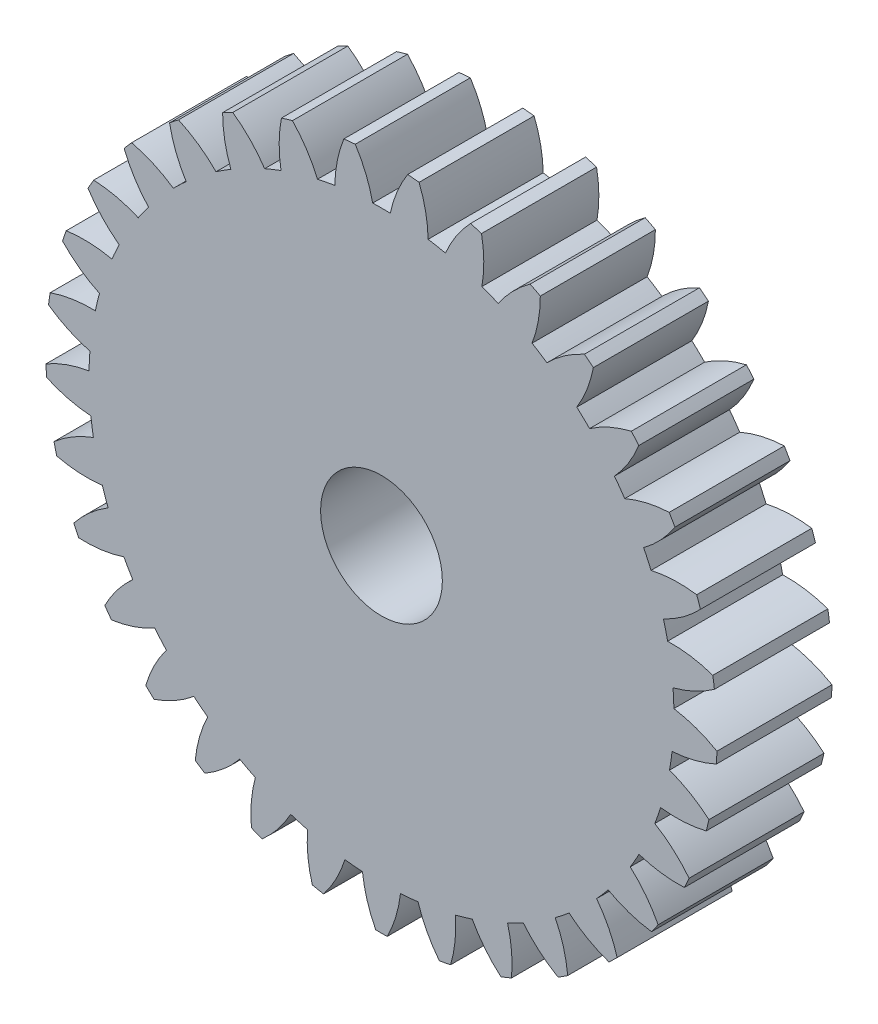
SolidWorks part; units mm, degrees
ref_plane "Alzado" through (0, 0, 0) normal (0, 0, 1) x (1, 0, 0)
ref_plane "Planta" through (0, 0, 0) normal (0, 1, 0) x (1, 0, 0)
ref_plane "Vista lateral" through (0, 0, 0) normal (1, 0, 0) x (0, 0, -1)
sketch "Croquis1" plane through (0, 0, 0) normal (0, 0, 1) x (1, 0, 0)
  line L0 (13.6206, 0) -> (-13.971, 0) construction
  line L1 (-0.46, 15.2421) -> (0, 0) construction
  line L2 (0.46, 15.2421) -> (0, 0) construction
  line L3 (1.3662, 17.4466) -> (0, 0) construction
  line L4 (1.9603, 17.3899) -> (0, 0) construction
  line L5 (0, -3.6901) -> (0, 21.5552) construction
  circle A0 centre (0, 0) radius 3.175
  arc A29 (2.4329, 15.0537) -> (1.9603, 17.3899) centre (-4.1661, 14.9347) ccw
  arc A30 (1.9603, 17.3899) -> (1.3662, 17.4466) centre (0, 0) ccw
  arc A31 (1.3662, 17.4466) -> (0.46, 15.2421) centre (6.9172, 13.8764) ccw
  arc A32 (0.46, 15.2421) -> (-0.46, 15.2421) centre (0, 0) ccw
  circle A133 centre (0, 0) radius 15.249 construction
  circle A134 centre (0, 0) radius 17.5 construction
  arc A135 (3.3363, 14.8796) -> (2.4329, 15.0537) centre (0, 0) ccw
  arc A136 (4.6433, 16.8728) -> (3.3363, 14.8796) centre (9.4183, 12.3166) ccw
  arc A137 (5.2159, 16.7046) -> (4.6433, 16.8728) centre (0, 0) ccw
  arc A138 (5.2378, 14.3212) -> (5.2159, 16.7046) centre (-1.2644, 15.4533) ccw
  arc A139 (6.092, 13.9793) -> (5.2378, 14.3212) centre (0, 0) ccw
  arc A140 (7.7526, 15.6891) -> (6.092, 13.9793) centre (11.5791, 10.3116) ccw
  arc A141 (8.283, 15.4156) -> (7.7526, 15.6891) centre (0, 0) ccw
  arc A142 (7.8535, 13.0712) -> (8.283, 15.4156) centre (1.683, 15.4133) ccw
  arc A143 (8.6275, 12.5737) -> (7.8535, 13.0712) centre (0, 0) ccw
  arc A144 (10.5816, 13.9384) -> (8.6275, 12.5737) centre (13.3213, 7.9339) ccw
  arc A145 (11.0508, 13.5695) -> (10.5816, 13.9384) centre (0, 0) ccw
  arc A146 (10.1853, 11.3487) -> (11.0508, 13.5695) centre (4.5696, 14.8163) ccw
  arc A147 (10.8512, 10.7137) -> (10.1853, 11.3487) centre (0, 0) ccw
  arc A148 (13.0283, 11.6839) -> (10.8512, 10.7137) centre (14.582, 5.2694) ccw
  arc A149 (13.4191, 11.2329) -> (13.0283, 11.6839) centre (0, 0) ccw
  arc A150 (12.149, 9.216) -> (13.4191, 11.2329) centre (7.291, 13.6837) ccw
  arc A151 (12.6827, 8.4665) -> (12.149, 9.216) centre (0, 0) ccw
  arc A152 (15.004, 9.0072) -> (12.6827, 8.4665) centre (15.3158, 2.4145) ccw
  arc A153 (15.3024, 8.4903) -> (15.004, 9.0072) centre (0, 0) ccw
  arc A154 (13.6736, 6.7502) -> (15.3024, 8.4903) centre (9.7489, 12.0566) ccw
  arc A155 (14.0558, 5.9133) -> (13.6736, 6.7502) centre (0, 0) ccw
  arc A156 (16.4375, 6.0049) -> (14.0558, 5.9133) centre (15.4959, -0.5276) ccw
  arc A157 (16.6327, 5.4409) -> (16.4375, 6.0049) centre (0, 0) ccw
  arc A158 (14.704, 4.0405) -> (16.6327, 5.4409) centre (11.8545, 9.9937) ccw
  arc A159 (14.9209, 3.1464) -> (14.704, 4.0405) centre (0, 0) ccw
  arc A160 (17.2769, 2.7855) -> (14.9209, 3.1464) centre (15.1161, -3.4507) ccw
  arc A161 (17.3618, 2.1948) -> (17.2769, 2.7855) centre (0, 0) ccw
  arc A162 (15.2029, 1.1848) -> (17.3618, 2.1948) centre (13.5316, 7.5696) ccw
  arc A163 (15.2467, 0.2657) -> (15.2029, 1.1848) centre (0, 0) ccw
  arc A164 (17.4918, -0.5345) -> (15.2467, 0.2657) centre (14.1898, -6.2491) ccw
  arc A165 (17.4634, -1.1306) -> (17.4918, -0.5345) centre (0, 0) ccw
  arc A166 (15.1524, -1.7138) -> (17.4634, -1.1306) centre (14.7196, 4.872) ccw
  arc A167 (15.0214, -2.6245) -> (15.1524, -1.7138) centre (0, 0) ccw
  arc A168 (17.0746, -3.8352) -> (15.0214, -2.6245) centre (12.7508, -8.8216) ccw
  arc A169 (16.9339, -4.4152) -> (17.0746, -3.8352) centre (0, 0) ccw
  arc A170 (14.5542, -4.5505) -> (16.9339, -4.4152) centre (15.3756, 1.9982) ccw
  arc A171 (14.2533, -5.4199) -> (14.5542, -4.5505) centre (0, 0) ccw
  arc A172 (16.0402, -6.9973) -> (14.2533, -5.4199) centre (10.8508, -11.0753) ccw
  arc A173 (15.7923, -7.5401) -> (16.0402, -6.9973) centre (0, 0) ccw
  arc A174 (13.43, -7.2226) -> (15.7923, -7.5401) centre (15.4759, -0.9477) ccw
  arc A175 (12.97, -8.0194) -> (13.43, -7.2226) centre (0, 0) ccw
  arc A176 (14.4261, -9.9064) -> (12.97, -8.0194) centre (8.5587, -12.9287) ccw
  arc A177 (14.0799, -10.3926) -> (14.4261, -9.9064) centre (0, 0) ccw
  arc A178 (11.8204, -9.6338) -> (14.0799, -10.3926) centre (15.0169, -3.8594) ccw
  arc A179 (11.2179, -10.3291) -> (11.8204, -9.6338) centre (0, 0) ccw
  arc A180 (12.2906, -12.4576) -> (11.2179, -10.3291) centre (5.9573, -14.3148) ccw
  arc A181 (11.8587, -12.8694) -> (12.2906, -12.4576) centre (0, 0) ccw
  arc A182 (9.7836, -11.6967) -> (11.8587, -12.8694) centre (14.0151, -6.6317) ccw
  arc A183 (9.0604, -12.2654) -> (9.7836, -11.6967) centre (0, 0) ccw
  arc A184 (9.7109, -14.5585) -> (9.0604, -12.2654) centre (3.1405, -15.1835) ccw
  arc A185 (9.2088, -14.8811) -> (9.7109, -14.5585) centre (0, 0) ccw
  arc A186 (7.3932, -13.3369) -> (9.2088, -14.8811) centre (12.5068, -9.1642) ccw
  arc A187 (6.5754, -13.7585) -> (7.3932, -13.3369) centre (0, 0) ccw
  arc A188 (6.7802, -16.1332) -> (6.5754, -13.7585) centre (0.2103, -15.5035) ccw
  arc A189 (6.2261, -16.355) -> (6.7802, -16.1332) centre (0, 0) ccw
  arc A190 (4.7356, -14.495) -> (6.2261, -16.355) centre (10.5465, -11.3655) ccw
  arc A191 (3.8528, -14.7543) -> (4.7356, -14.495) centre (0, 0) ccw
  arc A192 (3.6044, -17.1248) -> (3.8528, -14.7543) centre (-2.7276, -15.2631) ccw
  arc A193 (3.0184, -17.2377) -> (3.6044, -17.1248) centre (0, 0) ccw
  arc A194 (1.9068, -15.1293) -> (3.0184, -17.2377) centre (8.2049, -13.1561) ccw
  arc A195 (0.9909, -15.2168) -> (1.9068, -15.1293) centre (0, 0) ccw
  arc A196 (0.2984, -17.4975) -> (0.9909, -15.2168) centre (-5.5668, -14.4711) ccw
  arc A197 (-0.2984, -17.4975) -> (0.2984, -17.4975) centre (0, 0) ccw
  arc A198 (-0.9909, -15.2168) -> (-0.2984, -17.4975) centre (5.5668, -14.4711) ccw
  arc A199 (-1.9068, -15.1293) -> (-0.9909, -15.2168) centre (0, 0) ccw
  arc A200 (-3.0184, -17.2377) -> (-1.9068, -15.1293) centre (-8.2049, -13.1561) ccw
  arc A201 (-3.6044, -17.1248) -> (-3.0184, -17.2377) centre (0, 0) ccw
  arc A202 (-3.8528, -14.7543) -> (-3.6044, -17.1248) centre (2.7276, -15.2631) ccw
  arc A203 (-4.7356, -14.495) -> (-3.8528, -14.7543) centre (0, 0) ccw
  arc A204 (-6.2261, -16.355) -> (-4.7356, -14.495) centre (-10.5465, -11.3655) ccw
  arc A205 (-6.7802, -16.1332) -> (-6.2261, -16.355) centre (0, 0) ccw
  arc A206 (-6.5754, -13.7585) -> (-6.7802, -16.1332) centre (-0.2103, -15.5035) ccw
  arc A207 (-7.3932, -13.3369) -> (-6.5754, -13.7585) centre (0, 0) ccw
  arc A208 (-9.2088, -14.8811) -> (-7.3932, -13.3369) centre (-12.5068, -9.1642) ccw
  arc A209 (-9.7109, -14.5585) -> (-9.2088, -14.8811) centre (0, 0) ccw
  arc A210 (-9.0604, -12.2654) -> (-9.7109, -14.5585) centre (-3.1405, -15.1835) ccw
  arc A211 (-9.7836, -11.6967) -> (-9.0604, -12.2654) centre (0, 0) ccw
  arc A212 (-11.8587, -12.8694) -> (-9.7836, -11.6967) centre (-14.0151, -6.6317) ccw
  arc A213 (-12.2906, -12.4576) -> (-11.8587, -12.8694) centre (0, 0) ccw
  arc A214 (-11.2179, -10.3291) -> (-12.2906, -12.4576) centre (-5.9573, -14.3148) ccw
  arc A215 (-11.8204, -9.6338) -> (-11.2179, -10.3291) centre (0, 0) ccw
  arc A216 (-14.0799, -10.3926) -> (-11.8204, -9.6338) centre (-15.0169, -3.8594) ccw
  arc A217 (-14.4261, -9.9064) -> (-14.0799, -10.3926) centre (0, 0) ccw
  arc A218 (-12.97, -8.0194) -> (-14.4261, -9.9064) centre (-8.5587, -12.9287) ccw
  arc A219 (-13.43, -7.2226) -> (-12.97, -8.0194) centre (0, 0) ccw
  arc A220 (-15.7923, -7.5401) -> (-13.43, -7.2226) centre (-15.4759, -0.9477) ccw
  arc A221 (-16.0402, -6.9973) -> (-15.7923, -7.5401) centre (0, 0) ccw
  arc A222 (-14.2533, -5.4199) -> (-16.0402, -6.9973) centre (-10.8508, -11.0753) ccw
  arc A223 (-14.5542, -4.5505) -> (-14.2533, -5.4199) centre (0, 0) ccw
  arc A224 (-16.9339, -4.4152) -> (-14.5542, -4.5505) centre (-15.3756, 1.9982) ccw
  arc A225 (-17.0746, -3.8352) -> (-16.9339, -4.4152) centre (0, 0) ccw
  arc A226 (-15.0214, -2.6245) -> (-17.0746, -3.8352) centre (-12.7508, -8.8216) ccw
  arc A227 (-15.1524, -1.7138) -> (-15.0214, -2.6245) centre (0, 0) ccw
  arc A228 (-17.4634, -1.1306) -> (-15.1524, -1.7138) centre (-14.7196, 4.872) ccw
  arc A229 (-17.4918, -0.5345) -> (-17.4634, -1.1306) centre (0, 0) ccw
  arc A230 (-15.2467, 0.2657) -> (-17.4918, -0.5345) centre (-14.1898, -6.2491) ccw
  arc A231 (-15.2029, 1.1848) -> (-15.2467, 0.2657) centre (0, 0) ccw
  arc A232 (-17.3618, 2.1948) -> (-15.2029, 1.1848) centre (-13.5316, 7.5696) ccw
  arc A233 (-17.2769, 2.7855) -> (-17.3618, 2.1948) centre (0, 0) ccw
  arc A234 (-14.9209, 3.1464) -> (-17.2769, 2.7855) centre (-15.1161, -3.4507) ccw
  arc A235 (-14.704, 4.0405) -> (-14.9209, 3.1464) centre (0, 0) ccw
  arc A236 (-16.6327, 5.4409) -> (-14.704, 4.0405) centre (-11.8545, 9.9937) ccw
  arc A237 (-16.4375, 6.0049) -> (-16.6327, 5.4409) centre (0, 0) ccw
  arc A238 (-14.0558, 5.9133) -> (-16.4375, 6.0049) centre (-15.4959, -0.5276) ccw
  arc A239 (-13.6736, 6.7502) -> (-14.0558, 5.9133) centre (0, 0) ccw
  arc A240 (-15.3024, 8.4903) -> (-13.6736, 6.7502) centre (-9.7489, 12.0566) ccw
  arc A241 (-15.004, 9.0072) -> (-15.3024, 8.4903) centre (0, 0) ccw
  arc A242 (-12.6827, 8.4665) -> (-15.004, 9.0072) centre (-15.3158, 2.4145) ccw
  arc A243 (-12.149, 9.216) -> (-12.6827, 8.4665) centre (0, 0) ccw
  arc A244 (-13.4191, 11.2329) -> (-12.149, 9.216) centre (-7.291, 13.6837) ccw
  arc A245 (-13.0283, 11.6839) -> (-13.4191, 11.2329) centre (0, 0) ccw
  arc A246 (-10.8512, 10.7137) -> (-13.0283, 11.6839) centre (-14.582, 5.2694) ccw
  arc A247 (-10.1853, 11.3487) -> (-10.8512, 10.7137) centre (0, 0) ccw
  arc A248 (-11.0508, 13.5695) -> (-10.1853, 11.3487) centre (-4.5696, 14.8163) ccw
  arc A249 (-10.5816, 13.9384) -> (-11.0508, 13.5695) centre (0, 0) ccw
  arc A250 (-8.6275, 12.5737) -> (-10.5816, 13.9384) centre (-13.3213, 7.9339) ccw
  arc A251 (-7.8535, 13.0712) -> (-8.6275, 12.5737) centre (0, 0) ccw
  arc A252 (-8.283, 15.4156) -> (-7.8535, 13.0712) centre (-1.683, 15.4133) ccw
  arc A253 (-7.7526, 15.6891) -> (-8.283, 15.4156) centre (0, 0) ccw
  arc A254 (-6.092, 13.9793) -> (-7.7526, 15.6891) centre (-11.5791, 10.3116) ccw
  arc A255 (-5.2378, 14.3212) -> (-6.092, 13.9793) centre (0, 0) ccw
  arc A256 (-5.2159, 16.7046) -> (-5.2378, 14.3212) centre (1.2644, 15.4533) ccw
  arc A257 (-4.6433, 16.8728) -> (-5.2159, 16.7046) centre (0, 0) ccw
  arc A258 (-3.3363, 14.8796) -> (-4.6433, 16.8728) centre (-9.4183, 12.3166) ccw
  arc A259 (-2.4329, 15.0537) -> (-3.3363, 14.8796) centre (0, 0) ccw
  arc A260 (-1.9603, 17.3899) -> (-2.4329, 15.0537) centre (4.1661, 14.9347) ccw
  arc A261 (-1.3662, 17.4466) -> (-1.9603, 17.3899) centre (0, 0) ccw
  arc A262 (-0.46, 15.2421) -> (-1.3662, 17.4466) centre (-6.9172, 13.8764) ccw
  point P244 (0, 0)
  dimension "D1" = 6.35
  dimension "D2" = 88.271
  dimension "D3" = 35
  dimension "D8" = 6.9172
  dimension "D11" = 30.498
  dimension "D4" = 91.729
  dimension "D5" = 94.477
  dimension "D6" = 96.432
  dimension "D7" = 13.8764
  dimension "D9" = 4.1661
  dimension "D10" = 14.9347
  dimension "D12" = 33
extrude "Saliente-Extruir1" add sketch "Croquis1" along normal blind 6
sketch "Croquis2" plane through (0, 0, 0) normal (0, 0, -1) x (-1, 0, 0)
  circle A0 centre (0, 0) radius 6
  circle A1 centre (0, 0) radius 3.175
  dimension "D1" = 12
  dimension "D2" = 6.35
extrude "Saliente-Extruir2" add sketch "Croquis2" along normal blind 5.5
